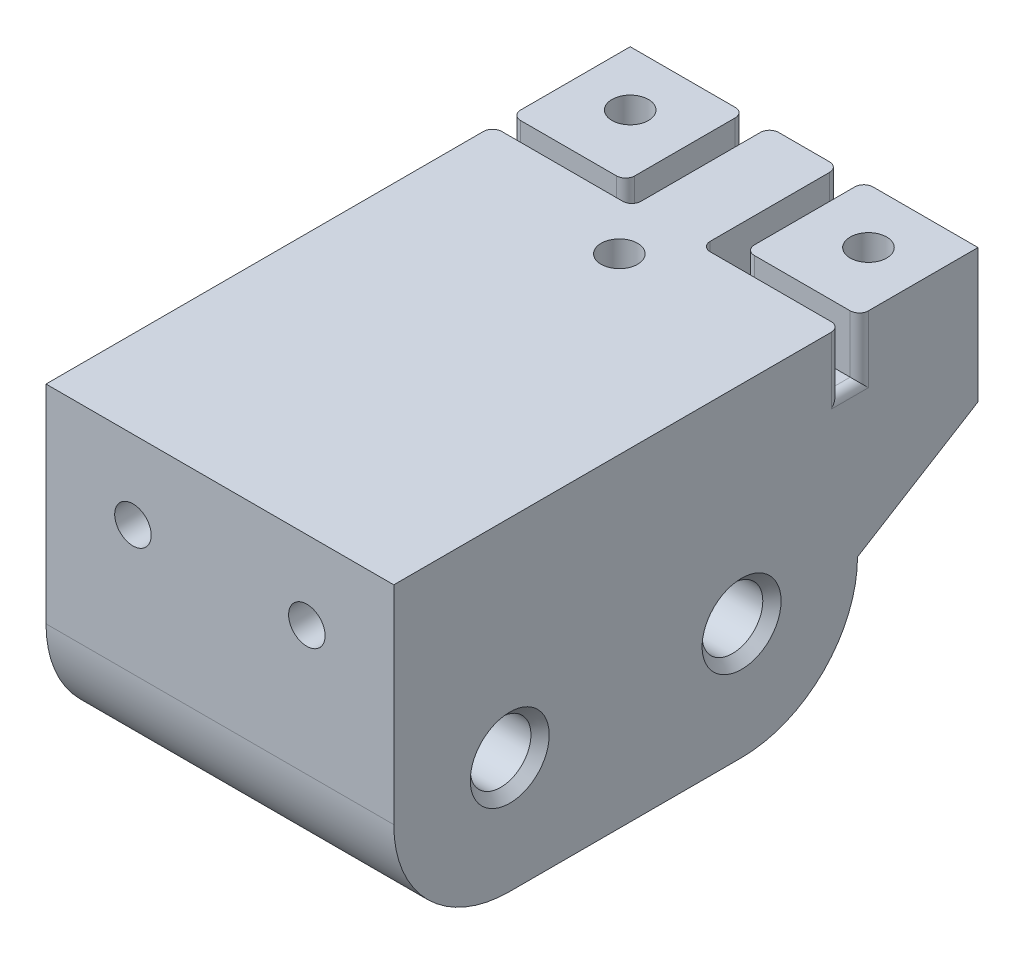
SolidWorks part; units mm, degrees
ref_plane "Front Plane" through (0, 0, 0) normal (0, 0, 1) x (1, 0, 0)
ref_plane "Top Plane" through (0, 0, 0) normal (0, 1, 0) x (1, 0, 0)
ref_plane "Right Plane" through (0, 0, 0) normal (1, 0, 0) x (0, 0, -1)
sketch "Sketch1" plane through (0, 0, 0) normal (1, 0, 0) x (0, 0, -1)
  line L0 (25.4, 22.75) -> (25.4, 0) construction
  line L1 (0, 22.75) -> (50.8, 22.75)
  line L2 (0, 22.75) -> (0, 0)
  line L3 (0, 0) -> (50.8, 0)
  line L4 (50.8, 22.75) -> (64, 22.75)
  line L6 (64, 22.75) -> (64, 8.1076)
  line L7 (64, 8.1076) -> (50.8, 0)
  circle A0 centre (12.7, 0) radius 3.325
  circle A1 centre (38.1, 0) radius 3.325
  circle A2 centre (12.7, 0) radius 12.7
  circle A3 centre (38.1, 0) radius 12.7
  point P10 (0, 0)
  dimension "D1" = 6.65
  dimension "D6" = 25.4
  dimension "D2" = 25.4
  dimension "D4" = 12.7
  dimension "D5" = 22.75
  dimension "D3" = 13.2
  dimension "D7" = 50.8
  dimension "D8" = 15.4911
extrude "Boss-Extrude2" add sketch "Sketch1" along normal blind 38.1
ref_plane "Plane1" through (0, -12.7, 0) normal (0, -1, 0) x (-1, 0, 0)
sketch "Sketch6" plane through (0, -12.7, 0) normal (0, -1, 0) x (-1, 0, 0)
  line L0 (-38.1, 38.1) -> (0, 38.1)
  line L1 (-38.1, 50.8) -> (-38.1, 25.4) construction
  line L2 (0, 25.4) -> (0, 50.8) construction
  line L3 (-38.1, 12.7) -> (0, 12.7)
  line L4 (-38.1, 25.4) -> (-38.1, 0) construction
  line L5 (0, 0) -> (0, 25.4) construction
  line L7 (-38.1, 38.1) -> (0, 38.1)
  line L8 (-38.1, 38.1) -> (-38.1, 12.7)
  line L9 (-38.1, 12.7) -> (0, 12.7)
  line L10 (0, 38.1) -> (0, 12.7)
extrude "Boss-Extrude3" add sketch "Sketch6" against normal up to next
sketch "Sketch10" plane through (0, 0, 0) normal (0, 0, 1) x (1, 0, 0)
  line L0 (38.1, 22.75) -> (38.1, 0) construction
  line L1 (0, 22.75) -> (38.1, 22.75)
  line L2 (0, 22.75) -> (0, 5.5563)
  line L3 (0, 5.5563) -> (38.1, 5.5563)
  line L4 (38.1, 22.75) -> (38.1, 5.5563)
  line L5 (19.05, 22.75) -> (19.05, 5.5563) construction
  line L6 (0, 14.1531) -> (19.05, 14.1531) construction
  line L7 (19.05, 14.1531) -> (38.1, 14.1531) construction
  circle A0 centre (9.525, 14.1531) radius 2
  circle A1 centre (28.575, 14.1531) radius 2
  dimension "D2" = 4
  dimension "D1" = 17.1937
extrude "Cut-Extrude6" cut sketch "Sketch10" against normal blind 8 contours A0 | A1
chamfer "Chamfer1" distance 1 angle 45 4 edges at (38.1, 0, -16.025) (0, 0, -16.025) (38.1, 0, -41.425) (0, 0, -41.425)
sketch "Sketch15" plane through (0, 22.75, 0) normal (0, 1, 0) x (1, 0, 0)
  line L0 (0, 64) -> (38.1, 64) construction
  line L5 (0, 50.995) -> (12.5, 50.995)
  line L6 (12.5, 50.995) -> (12.5, 64)
  line L8 (15.26, 64) -> (15.26, 48.925)
  line L9 (15.26, 48.925) -> (0, 48.925)
  line L12 (19.05, 38.6) -> (19.05, 64) construction
  line L14 (22.84, 48.925) -> (38.1, 48.925)
  line L15 (22.84, 64) -> (22.84, 48.925)
  line L17 (25.6, 50.995) -> (25.6, 64)
  line L18 (38.1, 50.995) -> (25.6, 50.995)
  line L20 (0, 64) -> (38.1, 64)
  line L21 (0, 64) -> (0, 38.6)
  line L22 (0, 38.6) -> (38.1, 38.6)
  line L23 (38.1, 64) -> (38.1, 38.6)
  line L25 (0, 48.925) -> (0, 38.6) construction
  point P4 (0, 0)
  point P9 (0, 0)
  point P12 (0, 0)
  point P22 (0, 0)
  point P23 (0, 0)
  point P24 (0, 0)
  point P25 (0, 0)
  point P26 (0, 0)
  point P27 (0, 0)
  point P28 (0, 52.9003)
  point P29 (0, 0)
  point P30 (0, 0)
  point P31 (0, 0)
  point P32 (0, 0)
  point P33 (0, 62.5)
  point P35 (13.8887, 62.1843)
  dimension "D1" = 25.4
  dimension "D2" = 10.325
  dimension "D6" = 15.26
  dimension "D8" = 13.005
  dimension "D4" = 12.395
  dimension "D5" = 12.5
  dimension "D7" = 38.1
  dimension "D9" = 15.075
extrude "Cut-Extrude9" cut sketch "Sketch15" against normal blind 6.3
fillet "Fillet3" radius 1 16 edges at (25.6, 19.6, -50.995) (22.84, 19.6, -48.925) (15.26, 19.6, -48.925) (12.5, 19.6, -50.995) (38.1, 19.6, -48.925) (38.1, 16.45, -49.96) (38.1, 19.6, -50.995) (0, 19.6, -50.995) (0, 16.45, -49.96) (0, 19.6, -48.925) (25.6, 19.6, -64) (24.22, 16.45, -64) (22.84, 19.6, -64) (15.26, 19.6, -64) (13.88, 16.45, -64) (12.5, 19.6, -64)
sketch "Sketch16" plane through (0, 22.75, 0) normal (0, 1, 0) x (1, 0, 0)
  line L0 (19.05, 64) -> (19.05, 38.6) construction
  line L1 (0, 64) -> (38.1, 64)
  line L2 (0, 64) -> (0, 38.6)
  line L3 (0, 38.6) -> (38.1, 38.6)
  line L4 (38.1, 64) -> (38.1, 38.6)
  line L5 (11.5, 64) -> (0, 64) construction
  line L6 (0, 51.995) -> (0, 64) construction
  circle A0 centre (19.05, 43.76) radius 2
  circle A1 centre (6, 58) radius 2
  circle A2 centre (32.1, 58) radius 2
  point P5 (0, 50.8)
  point P13 (0, 0)
  point P15 (0, 62.5)
  dimension "D6" = 4
  dimension "D1" = 25.4
  dimension "D2" = 38.1
  dimension "D3" = 5.16
  dimension "D4" = 6
  dimension "D5" = 6
extrude "Cut-Extrude10" cut sketch "Sketch16" against normal blind 5 contours A2 | L0 A0 | A0 L0 | A1
equation "\"Ø Smaller Shaft\"=6.35"
equation "\"Shaft Distance\"= 25.4"
equation "\"Width\"= \"Ø Smaller Shaft\" * 2 + \"Shaft Distance\" + \"Width End\" * 2"
equation "\"Width End\"= 6.35"
equation "\"Length\"= 38.1"
equation "\"Rod to Belt\"= 31.75 + 3"
equation "\"Nom Tolerance\"= 0.15"
equation "\"D1@Sketch1\"=\"Ø Smaller Shaft\" + \"Nom Tolerance\"*2"
equation "\"D2@Sketch1\"=\"Shaft Distance\""
equation "\"D4@Sketch1\"=\"Shaft Distance\"/2"
equation "\"Belt\"= 6"
equation "\"Belt Thickness\"=1.38"
equation "\"Ø Pulley\"= 10.9"
equation "\"Pully Distance\"= 35"
equation "\"D6@Sketch1\"=\"Ø Smaller Shaft\"*4"
equation "\"D5@Sketch1\"=\"Rod to Belt\"+(\"Belt\"/2)-15"
equation "\"D1@Boss-Extrude2\"=\"Length\""
equation "\"Ø Outer Washer\"=12.7"
equation "\"Washer Thickness\"=2"
equation "\"D1\"= \"Washer Thickness\""
equation "\"M3 Heated Insert Hole\"= 4"
equation "\"D1@Sketch10\"=\"Rod to Belt\"+(\"Belt\"/2)-15-(\"Ø Smaller Shaft\"*1.75)/2"
equation "\"D2@Sketch10\"=\"M3 Heated Insert Hole\""
equation "\"Ø Graphite Holder\"= 17"
